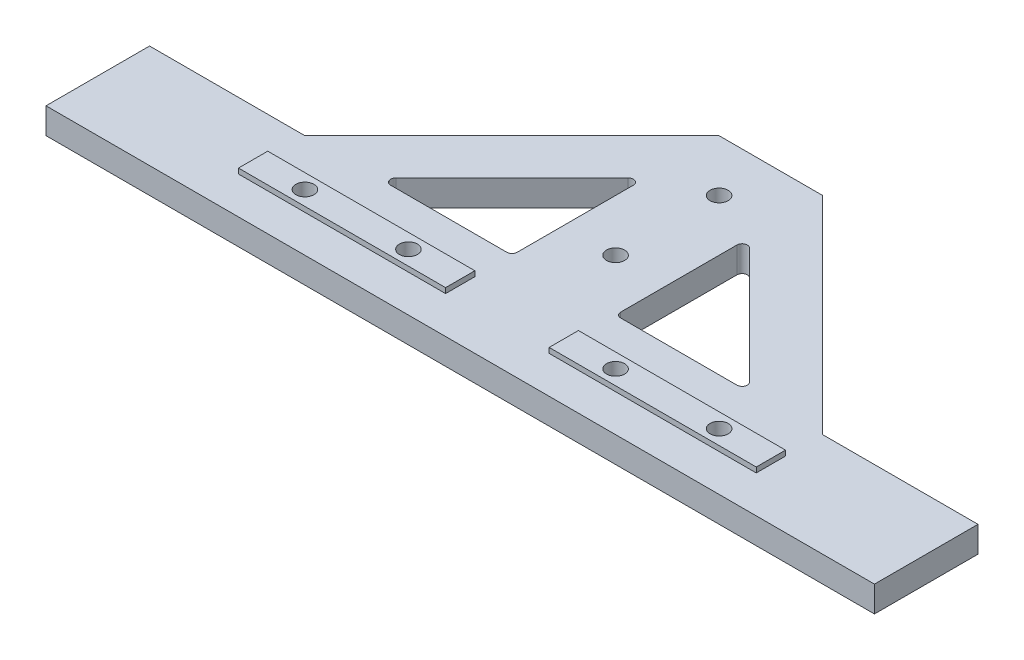
SolidWorks part; units mm, degrees
ref_plane "Plano frontal" through (0, 0, 0) normal (0, 0, 1) x (1, 0, 0)
ref_plane "Plano superior" through (0, 0, 0) normal (0, 1, 0) x (1, 0, 0)
ref_plane "Plano direito" through (0, 0, 0) normal (1, 0, 0) x (0, 0, -1)
sketch "Esboço1" plane through (0, 0, 0) normal (0, 1, 0) x (1, 0, 0)
  line L0 (-50, 0) -> (-50, 20)
  line L1 (-10, 60) -> (10, 60)
  line L2 (10, 60) -> (50, 20)
  line L3 (50, 20) -> (50, 0)
  line L4 (50, 0) -> (-50, 0)
  line L5 (-10, 43.4437) -> (-10, 21)
  line L6 (-33.4437, 20) -> (-11, 20)
  line L7 (-11.7071, 44.1508) -> (-34.1508, 21.7071)
  line L8 (0, 60) -> (0, 0) construction
  line L9 (-50, 10) -> (50, 10) construction
  line L10 (-10, 60) -> (-50, 20)
  line L11 (11.7071, 44.1508) -> (34.1508, 21.7071)
  line L12 (33.4437, 20) -> (11, 20)
  line L13 (10, 43.4437) -> (10, 21)
  arc A0 (-10, 21) -> (-11, 20) centre (-11, 21) cw
  arc A1 (-33.4437, 20) -> (-34.1508, 21.7071) centre (-33.4437, 21) cw
  arc A2 (-11.7071, 44.1508) -> (-10, 43.4437) centre (-11, 43.4437) cw
  circle A3 centre (-40, 10) radius 1.75
  circle A4 centre (-20, 10) radius 1.75
  circle A5 centre (0, 50) radius 1.75
  circle A6 centre (0, 30) radius 1.75
  circle A7 centre (20, 10) radius 1.75
  circle A8 centre (40, 10) radius 1.75
  arc A9 (11.7071, 44.1508) -> (10, 43.4437) centre (11, 43.4437) ccw
  arc A10 (33.4437, 20) -> (34.1508, 21.7071) centre (33.4437, 21) ccw
  arc A11 (10, 21) -> (11, 20) centre (11, 21) ccw
  dimension "D1" = 1
  dimension "D2" = 3.5
  dimension "D3" = 10
  dimension "D4" = 20
  dimension "D5" = 10
  dimension "D6" = 10
  dimension "D7" = 10
  dimension "D8" = 10
  dimension "D9" = 45
  dimension "D10" = 60
  dimension "D11" = 20
  dimension "D12" = 100
  dimension "D13" = 20
extrude "Ressalto-extrusão1" add sketch "Esboço1" along normal blind 5
sketch "Esboço3" plane through (0, 5, 0) normal (0, 1, 0) x (1, 0, 0)
  line L0 (-40, 10) -> (-20, 10) construction
  line L1 (-50, 20) -> (-50, 0) construction
  line L2 (-10, 7.175) -> (-50, 7.175)
  line L3 (-10, 7.175) -> (-10, 12.825)
  line L4 (-10, 12.825) -> (-50, 12.825)
  line L5 (-50, 7.175) -> (-50, 12.825)
  line L6 (-10, 7.175) -> (-50, 12.825) construction
  line L7 (-10, 12.825) -> (-50, 7.175) construction
  line L8 (20, 10) -> (40, 10) construction
  line L9 (50, 0) -> (50, 20) construction
  line L10 (10, 12.825) -> (50, 12.825)
  line L11 (10, 12.825) -> (10, 7.175)
  line L12 (10, 7.175) -> (50, 7.175)
  line L13 (50, 12.825) -> (50, 7.175)
  line L14 (10, 12.825) -> (50, 7.175) construction
  line L15 (10, 7.175) -> (50, 12.825) construction
  point P4 (-30, 10)
  point P17 (30, 10)
  circle M10 centre (40, 10) radius 1.75
  circle M11 centre (20, 10) radius 1.75
  circle M13 centre (-20, 10) radius 1.75
  circle M14 centre (-40, 10) radius 1.75
  line M22 (50, 0) -> (50, 20)
  line M26 (-50, 20) -> (-50, 0)
  dimension "D1" = 5.65
extrude "Ressalto-extrusão2" add sketch "Esboço3" along normal blind 1 contours L3 L4 L2 M26 M13 M14 | L11 L12 L10 M22 M11 M10
sketch "Esboço4" plane through (0, 0, 0) normal (0, -1, 0) x (1, 0, 0)
  line L0 (-50, -20) -> (-80, -20)
  line L1 (-80, -20) -> (-80, 0)
  line L2 (-80, 0) -> (-50, 0)
  line L3 (-50, 0) -> (-50, -20)
  line L4 (50, 0) -> (80, 0)
  line L5 (80, 0) -> (80, -20)
  line L6 (80, -20) -> (50, -20)
  line L7 (50, 0) -> (50, -20)
  line M10 (-50, 0) -> (-50, -20)
  line M14 (50, -20) -> (50, 0)
  dimension "D1" = 30
extrude "Ressalto-extrusão3" add sketch "Esboço4" against normal up to surface (5 mm away) contours L2 L1 L0 M10 | L6 L5 L4 M14 up to face at (18.4047, 5, -28.4048)
